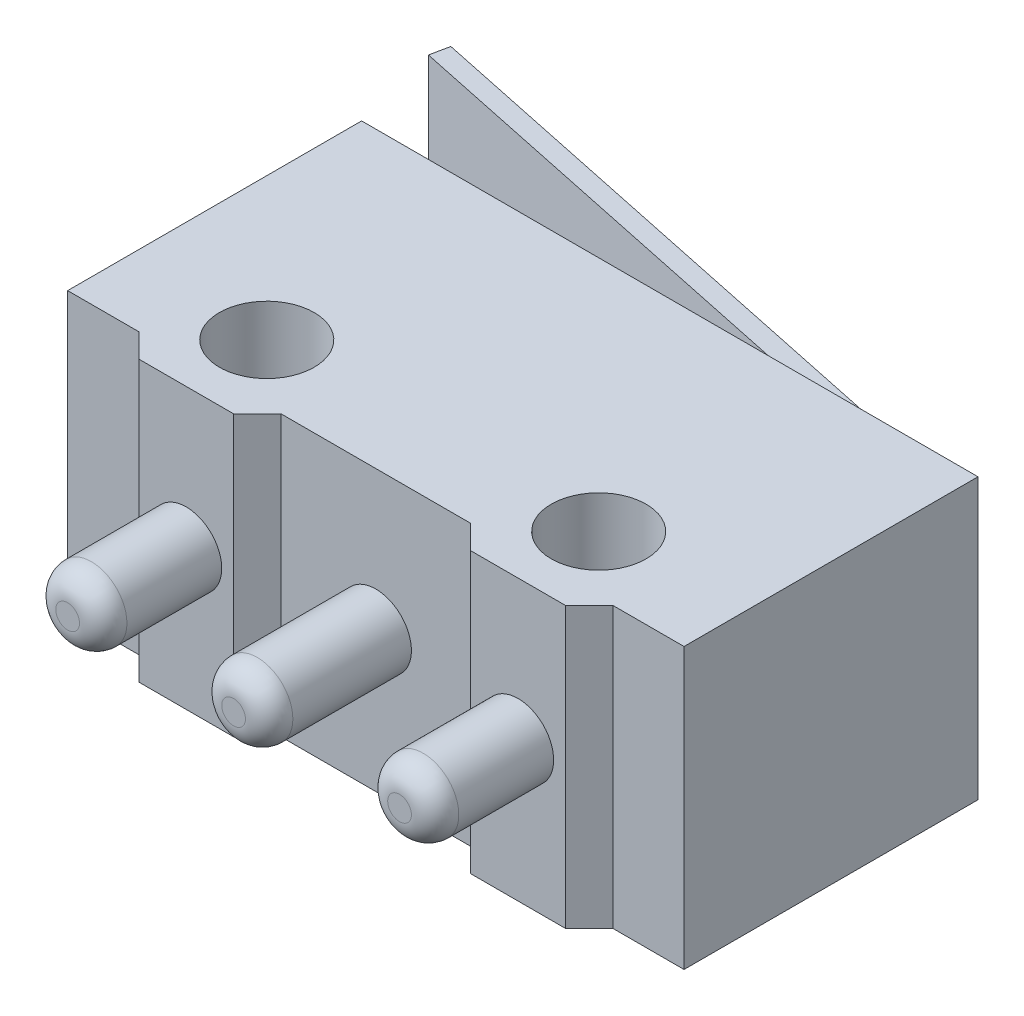
SolidWorks part; units mm, degrees
material "ABS"
ref_plane "Front Plane" through (0, 0, 0) normal (0, 0, 1) x (1, 0, 0)
ref_plane "Top Plane" through (0, 0, 0) normal (0, 1, 0) x (1, 0, 0)
ref_plane "Right Plane" through (0, 0, 0) normal (1, 0, 0) x (0, 0, -1)
sketch "Sketch1" plane through (0, 0, 0) normal (0, 1, 0) x (1, 0, 0)
  line L0 (0, 6.2373) -> (0, -4.4682) construction
  line L1 (-6.5, -3.1) -> (-5, -3.1)
  line L2 (-6.5, -3.1) -> (-6.5, 3.1)
  line L3 (-6.5, 3.1) -> (3.9559, 3.1)
  line L4 (6.5, -3.1) -> (6.5, 3.1)
  line L5 (-6.5, -3.1) -> (6.5, 3.1) construction
  line L6 (-6.5, 3.1) -> (6.5, -3.1) construction
  line L7 (3.5, -4.4182) -> (3.5, 0.05) construction
  line L8 (2.5, -3.6) -> (2, -3.1)
  line L9 (4.5, -3.6) -> (2.5, -3.6)
  line L10 (4.5, -3.6) -> (5, -3.1)
  line L11 (5, -3.1) -> (6.5, -3.1)
  line L12 (-2.5, -3.6) -> (-2, -3.1)
  line L13 (-4.5, -3.6) -> (-2.5, -3.6)
  line L14 (-4.5, -3.6) -> (-5, -3.1)
  line L15 (-2, -3.1) -> (2, -3.1)
  line L16 (5.9, 3.1) -> (-7.4177, 5.9)
  line L17 (-7.4177, 5.9) -> (-7.5, 5.5086)
  line L18 (-7.5, 5.5086) -> (3.9559, 3.1)
  line L19 (5.9, 3.1) -> (6.5, 3.1)
  circle A0 centre (3.5, -1.9) radius 1
  circle A1 centre (-3.5, -1.9) radius 1
  point P0 (0, 0)
  dimension "D3" = 2
  dimension "D1" = 13
  dimension "D2" = 6.2
  dimension "D4" = 3
  dimension "D5" = 0.5
  dimension "D6" = 5
  dimension "D7" = 2
  dimension "D8" = 135
  dimension "D9" = 14
  dimension "D10" = 9
  dimension "D11" = 0.4
  dimension "D12" = 0.6
extrude "Boss-Extrude1" add sketch "Sketch1" along normal mid plane 5.9
sketch "Sketch2" plane through (0, 2.95, 0) normal (0, 1, 0) x (1, 0, 0)
  line L0 (5.9, 3.1) -> (3.9559, 3.1)
  line L16 (6.5, 3.1) -> (5.9, 3.1)
  line L17 (5.9, 3.1) -> (-7.4177, 5.9)
  line L18 (-7.4177, 5.9) -> (-7.5, 5.5086)
  line L19 (-7.5, 5.5086) -> (3.9559, 3.1)
  line L20 (3.9559, 3.1) -> (-6.5, 3.1)
  line L21 (-6.5, 3.1) -> (-6.5, -3.1)
  line L22 (-6.5, -3.1) -> (-5, -3.1)
  line L23 (-5, -3.1) -> (-4.5, -3.6)
  line L24 (-4.5, -3.6) -> (-2.5, -3.6)
  line L25 (-2.5, -3.6) -> (-2, -3.1)
  line L26 (-2, -3.1) -> (2, -3.1)
  line L27 (2, -3.1) -> (2.5, -3.6)
  line L28 (2.5, -3.6) -> (4.5, -3.6)
  line L29 (4.5, -3.6) -> (5, -3.1)
  line L30 (5, -3.1) -> (6.5, -3.1)
  line L31 (6.5, -3.1) -> (6.5, 3.1)
  line L33 (5.9, 3.1) -> (-7.4177, 5.9)
  line L34 (-7.4177, 5.9) -> (-7.5, 5.5086)
  line L35 (-7.5, 5.5086) -> (3.9559, 3.1)
  dimension "D1" = 0
extrude "Cut-Extrude1" cut sketch "Sketch2" against normal blind 0.5
mirror "Mirror1" about plane through (0, 0, 0) normal (0, 1, 0) of "Cut-Extrude1"
sketch "Sketch3" plane through (0, 0, 3.1) normal (0, 0, 1) x (1, 0, 0)
  line L0 (0, 0) -> (0, 3.0921) construction
  line L1 (-4.5, 2.95) -> (-2.5, 2.95) construction
  circle A0 centre (0, 0) radius 0.75
  circle A1 centre (-3.5, 0) radius 0.75
  circle A2 centre (3.5, 0) radius 0.75
  point P10 (-3.5, 2.95)
  dimension "D1" = 1.5
extrude "Boss-Extrude2" add sketch "Sketch3" along normal blind 3
fillet "Fillet1" radius 0.5 3 edges at (2.75, 0, 6.1) (0.75, 0, 6.1) (-2.75, 0, 6.1)
sketch "Sketch7" plane through (0, 2.95, 0) normal (0, 1, 0) x (1, 0, 0)
  line L0 (-6.5, 0) -> (6.5, 0)
  line L1 (-6.5, 3.1) -> (-6.5, -3.1) construction
  line L2 (6.5, -3.1) -> (6.5, 3.1) construction
  line L3 (0, 3.1) -> (0, -3.1)
  line L4 (6.5, 3.1) -> (-6.5, 3.1) construction
  line L5 (-2, -3.1) -> (2, -3.1) construction
  line L6 (3.5, -1.9) -> (3.5, 3.1)
  line L7 (3.5, -1.9) -> (6.5, -1.9)
  line L8 (-6.5, 3.1) -> (-6.5, -3.1)
  line L9 (3.5, -1.9) -> (-6.5, -1.9)
  circle A0 centre (3.5, -1.9) radius 1 construction
  circle A1 centre (3.5, -1.9) radius 1
  circle A2 centre (-3.5, -1.9) radius 1 construction
  circle A3 centre (-3.5, -1.9) radius 1
  dimension "D3" = 2
  dimension "D1" = 5
  dimension "D2" = 3
sketch "Sketch8" plane through (0, 0, -3.1) normal (0, 0, -1) x (-1, 0, 0)
  line L0 (0, 2.95) -> (0, -2.95)
  line L1 (-6.5, -2.95) -> (6.5, -2.95) construction
  line L3 (-6.5, -2.95) -> (6.5, -2.95)
  dimension "D1" = 5.9
  dimension "D2" = 13
